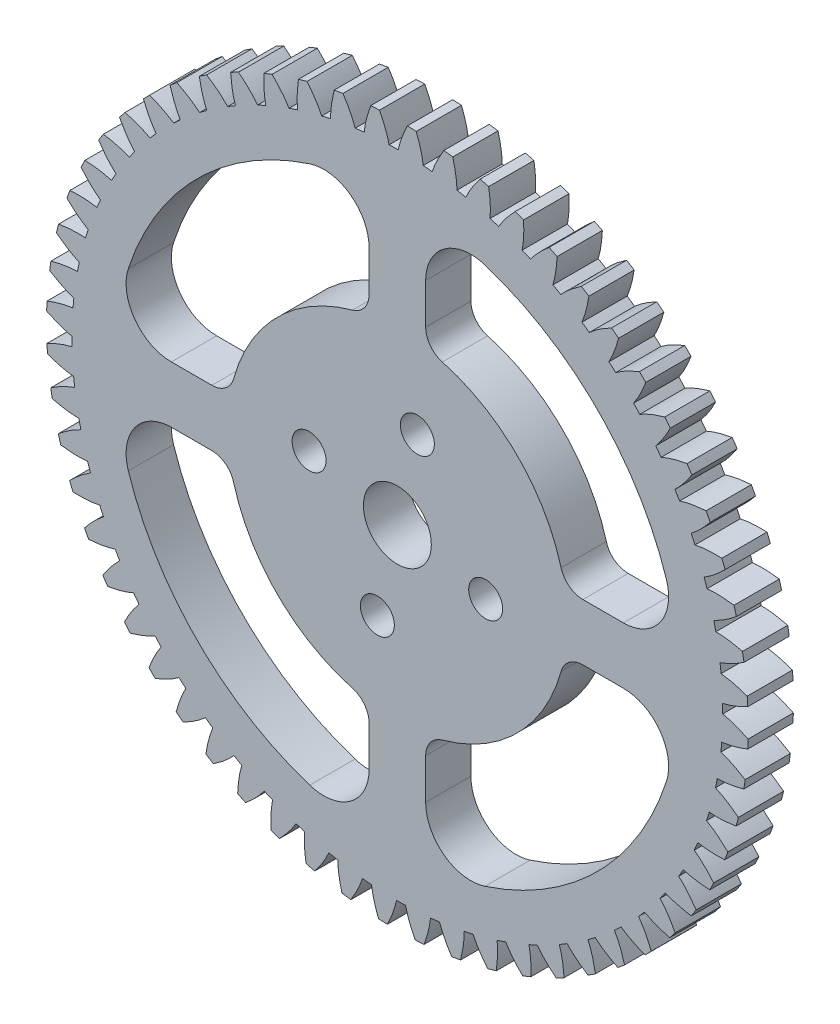
SolidWorks part; units mm, degrees
ref_plane "前视基准面" through (0, 0, 0) normal (0, 0, 1) x (1, 0, 0)
ref_plane "上视基准面" through (0, 0, 0) normal (0, 1, 0) x (1, 0, 0)
ref_plane "右视基准面" through (0, 0, 0) normal (1, 0, 0) x (0, 0, -1)
other "Configuration Table"
sketch "草图4" plane through (0, 0, 0) normal (0, 0, 1) x (1, 0, 0)
  line L0 (0, 0) -> (1.2733, 30.9738) construction
  line L1 (0, 0) -> (0.4471, 29.9967) construction
  line L2 (0, 0) -> (2.8926, 30.8648) construction
  circle A0 centre (0, 0) radius 30
  circle A1 centre (0, 0) radius 31
  circle A2 centre (0, 0) radius 28.75
  spline S0 degree 4 poles (0, 28.1908) (0.0005, 28.2136) (0.0035, 28.2777) (0.0153, 28.3985) (0.0434, 28.5946) (0.1142, 28.9567) (0.2601, 29.498) (0.4684, 30.082) (0.7305, 30.6867) (0.9882, 31.2083) (1.2086, 31.6182) (1.4921, 32.1066) (1.8568, 32.6819) (2.3141, 33.3354) (2.8753, 34.0567) (3.4818, 34.7632) (4.1191, 35.4414) (4.7852, 36.0922) (5.4762, 36.7151) (6.1025, 37.2372) (6.6509, 37.6668) (7.1192, 38.0155) (7.4936, 38.2848) (7.8829, 38.5536) (8.2582, 38.8052) (8.6695, 39.0687) (9.0299, 39.2939) (9.5696, 39.6154) (9.8959, 39.8017) (10.4233, 40.0948) (10.6619, 40.2173) (10.8772, 40.3318) (10.941, 40.3633) (10.9876, 40.3874) (11.0127, 40.4005) knots 0 0 0 0 0 0.005377 0.015084 0.028532 0.04661 0.092111 0.146842 0.174209 0.201575 0.228941 0.256307 0.307035 0.361767 0.4165 0.471232 0.525964 0.580697 0.635429 0.690161 0.717528 0.744894 0.77226 0.799626 0.826992 0.854358 0.881725 0.909091 0.954545 0.977273 0.988636 0.994318 1 1 1 1 1 construction
  spline S1 degree 4 poles (0.0751, 28.7499) (0.0864, 28.8057) (0.1395, 29.0504) (0.2668, 29.5168) (0.4673, 30.079) (0.6816, 30.574) (0.8307, 30.886) (0.8807, 30.9875) knots 0.033216 0.033216 0.033216 0.033216 0.033216 0.04661 0.092111 0.146842 0.173451 0.173451 0.173451 0.173451 0.173451
  spline S2 degree 4 poles (2.2849, 28.6591) (2.2782, 28.7156) (2.2453, 28.9638) (2.1567, 29.4391) (2.003, 30.0158) (1.8301, 30.5268) (1.7071, 30.85) (1.6656, 30.9552) knots 0.033216 0.033216 0.033216 0.033216 0.033216 0.04661 0.092111 0.146842 0.173451 0.173451 0.173451 0.173451 0.173451
  spline S3 degree 4 poles (3.0798, 28.5846) (3.0969, 28.6389) (3.1753, 28.8767) (3.3507, 29.3272) (3.6089, 29.8653) (3.8738, 30.3353) (4.0546, 30.63) (4.1149, 30.7257) knots 0.033216 0.033216 0.033216 0.033216 0.033216 0.04661 0.092111 0.146842 0.173451 0.173451 0.173451 0.173451 0.173451
  dimension "D1" = 60
  dimension "D2" = 62
  dimension "D3" = 57.5
  dimension "D5" = 1.5
  dimension "D6" = 4.5
sketch "草图6" plane through (0, 0, 0) normal (0, 0, 1) x (1, 0, 0)
  circle A0 centre (0, 0) radius 28.75 construction
  circle A1 centre (0, 0) radius 31 construction
  arc A2 (3.0798, 28.5846) -> (2.2849, 28.6591) centre (0, 0) ccw
  arc A3 (1.6656, 30.9552) -> (0.8807, 30.9875) centre (0, 0) ccw
  arc A4 (4.8922, 30.6115) -> (4.1149, 30.7257) centre (0, 0) ccw
  arc A5 (6.0509, 28.106) -> (5.268, 28.2632) centre (0, 0) ccw
  arc A6 (8.0652, 29.9325) -> (7.3041, 30.1272) centre (0, 0) ccw
  arc A7 (8.9556, 27.3196) -> (8.1935, 27.5577) centre (0, 0) ccw
  arc A8 (11.1498, 28.9255) -> (10.4132, 29.1987) centre (0, 0) ccw
  arc A9 (11.7622, 26.2338) -> (11.0292, 26.5503) centre (0, 0) ccw
  arc A10 (14.1123, 27.6015) -> (13.4083, 27.9503) centre (0, 0) ccw
  arc A11 (14.44, 24.8606) -> (13.744, 25.252) centre (0, 0) ccw
  arc A12 (16.9201, 25.9752) -> (16.2564, 26.3956) centre (0, 0) ccw
  arc A13 (16.9595, 23.215) -> (16.3083, 23.677) centre (0, 0) ccw
  arc A14 (19.5426, 24.0643) -> (18.9265, 24.5518) centre (0, 0) ccw
  arc A15 (19.2932, 21.3151) -> (18.6939, 21.8427) centre (0, 0) ccw
  arc A16 (21.9509, 21.8897) -> (21.3891, 22.4389) centre (0, 0) ccw
  arc A17 (21.4156, 19.1817) -> (20.8747, 19.769) centre (0, 0) ccw
  arc A18 (24.1187, 19.4753) -> (23.6175, 20.0802) centre (0, 0) ccw
  arc A19 (23.3033, 16.838) -> (22.8267, 17.4787) centre (0, 0) ccw
  arc A20 (26.0223, 16.8475) -> (25.587, 17.5015) centre (0, 0) ccw
  arc A21 (24.9357, 14.31) -> (24.5287, 14.9969) centre (0, 0) ccw
  arc A22 (27.6408, 14.0351) -> (27.2763, 14.7311) centre (0, 0) ccw
  arc A23 (26.2949, 11.6251) -> (25.9619, 12.3508) centre (0, 0) ccw
  arc A24 (28.9565, 11.069) -> (28.6667, 11.7992) centre (0, 0) ccw
  arc A25 (27.366, 8.8128) -> (27.1107, 9.5694) centre (0, 0) ccw
  arc A26 (29.9549, 7.9816) -> (29.743, 8.7381) centre (0, 0) ccw
  arc A27 (28.1373, 5.904) -> (27.9625, 6.6831) centre (0, 0) ccw
  arc A28 (30.6251, 4.8067) -> (30.4934, 5.5812) centre (0, 0) ccw
  arc A29 (28.6003, 2.9305) -> (28.5078, 3.7236) centre (0, 0) ccw
  arc A30 (30.9598, 1.5792) -> (30.9098, 2.3632) centre (0, 0) ccw
  arc A31 (28.7499, -0.0751) -> (28.7409, 0.7233) centre (0, 0) ccw
  arc A32 (30.9552, -1.6656) -> (30.9875, -0.8807) centre (0, 0) ccw
  arc A33 (28.5846, -3.0798) -> (28.6591, -2.2849) centre (0, 0) ccw
  arc A34 (30.6115, -4.8922) -> (30.7257, -4.1149) centre (0, 0) ccw
  arc A35 (28.106, -6.0509) -> (28.2632, -5.268) centre (0, 0) ccw
  arc A36 (29.9325, -8.0652) -> (30.1272, -7.3041) centre (0, 0) ccw
  arc A37 (27.3196, -8.9556) -> (27.5577, -8.1935) centre (0, 0) ccw
  arc A38 (28.9255, -11.1498) -> (29.1987, -10.4132) centre (0, 0) ccw
  arc A39 (26.2338, -11.7622) -> (26.5503, -11.0292) centre (0, 0) ccw
  arc A40 (27.6015, -14.1123) -> (27.9503, -13.4083) centre (0, 0) ccw
  arc A41 (24.8606, -14.44) -> (25.252, -13.744) centre (0, 0) ccw
  arc A42 (25.9752, -16.9201) -> (26.3956, -16.2564) centre (0, 0) ccw
  arc A43 (23.215, -16.9595) -> (23.677, -16.3083) centre (0, 0) ccw
  arc A44 (24.0643, -19.5426) -> (24.5518, -18.9265) centre (0, 0) ccw
  arc A45 (21.3151, -19.2932) -> (21.8427, -18.6939) centre (0, 0) ccw
  arc A46 (21.8897, -21.9509) -> (22.4389, -21.3891) centre (0, 0) ccw
  arc A47 (19.1817, -21.4156) -> (19.769, -20.8747) centre (0, 0) ccw
  arc A48 (19.4753, -24.1187) -> (20.0802, -23.6175) centre (0, 0) ccw
  arc A49 (16.838, -23.3033) -> (17.4787, -22.8267) centre (0, 0) ccw
  arc A50 (16.8475, -26.0223) -> (17.5015, -25.587) centre (0, 0) ccw
  arc A51 (14.31, -24.9357) -> (14.9969, -24.5287) centre (0, 0) ccw
  arc A52 (14.0351, -27.6408) -> (14.7311, -27.2763) centre (0, 0) ccw
  arc A53 (11.6251, -26.2949) -> (12.3508, -25.9619) centre (0, 0) ccw
  arc A54 (11.069, -28.9565) -> (11.7992, -28.6667) centre (0, 0) ccw
  arc A55 (8.8128, -27.366) -> (9.5694, -27.1107) centre (0, 0) ccw
  arc A56 (7.9816, -29.9549) -> (8.7381, -29.743) centre (0, 0) ccw
  arc A57 (5.904, -28.1373) -> (6.6831, -27.9625) centre (0, 0) ccw
  arc A58 (4.8067, -30.6251) -> (5.5812, -30.4934) centre (0, 0) ccw
  arc A59 (2.9305, -28.6003) -> (3.7236, -28.5078) centre (0, 0) ccw
  arc A60 (1.5792, -30.9598) -> (2.3632, -30.9098) centre (0, 0) ccw
  arc A61 (-0.0751, -28.7499) -> (0.7233, -28.7409) centre (0, 0) ccw
  arc A62 (-1.6656, -30.9552) -> (-0.8807, -30.9875) centre (0, 0) ccw
  arc A63 (-3.0798, -28.5846) -> (-2.2849, -28.6591) centre (0, 0) ccw
  arc A64 (-4.8922, -30.6115) -> (-4.1149, -30.7257) centre (0, 0) ccw
  arc A65 (-6.0509, -28.106) -> (-5.268, -28.2632) centre (0, 0) ccw
  arc A66 (-8.0652, -29.9325) -> (-7.3041, -30.1272) centre (0, 0) ccw
  arc A67 (-8.9556, -27.3196) -> (-8.1935, -27.5577) centre (0, 0) ccw
  arc A68 (-11.1498, -28.9255) -> (-10.4132, -29.1987) centre (0, 0) ccw
  arc A69 (-11.7622, -26.2338) -> (-11.0292, -26.5503) centre (0, 0) ccw
  arc A70 (-14.1123, -27.6015) -> (-13.4083, -27.9503) centre (0, 0) ccw
  arc A71 (-14.44, -24.8606) -> (-13.744, -25.252) centre (0, 0) ccw
  arc A72 (-16.9201, -25.9752) -> (-16.2564, -26.3956) centre (0, 0) ccw
  arc A73 (-16.9595, -23.215) -> (-16.3083, -23.677) centre (0, 0) ccw
  arc A74 (-19.5426, -24.0643) -> (-18.9265, -24.5518) centre (0, 0) ccw
  arc A75 (-19.2932, -21.3151) -> (-18.6939, -21.8427) centre (0, 0) ccw
  arc A76 (-21.9509, -21.8897) -> (-21.3891, -22.4389) centre (0, 0) ccw
  arc A77 (-21.4156, -19.1817) -> (-20.8747, -19.769) centre (0, 0) ccw
  arc A78 (-24.1187, -19.4753) -> (-23.6175, -20.0802) centre (0, 0) ccw
  arc A79 (-23.3033, -16.838) -> (-22.8267, -17.4787) centre (0, 0) ccw
  arc A80 (-26.0223, -16.8475) -> (-25.587, -17.5015) centre (0, 0) ccw
  arc A81 (-24.9357, -14.31) -> (-24.5287, -14.9969) centre (0, 0) ccw
  arc A82 (-27.6408, -14.0351) -> (-27.2763, -14.7311) centre (0, 0) ccw
  arc A83 (-26.2949, -11.6251) -> (-25.9619, -12.3508) centre (0, 0) ccw
  arc A84 (-28.9565, -11.069) -> (-28.6667, -11.7992) centre (0, 0) ccw
  arc A85 (-27.366, -8.8128) -> (-27.1107, -9.5694) centre (0, 0) ccw
  arc A86 (-29.9549, -7.9816) -> (-29.743, -8.7381) centre (0, 0) ccw
  arc A87 (-28.1373, -5.904) -> (-27.9625, -6.6831) centre (0, 0) ccw
  arc A88 (-30.6251, -4.8067) -> (-30.4934, -5.5812) centre (0, 0) ccw
  arc A89 (-28.6003, -2.9305) -> (-28.5078, -3.7236) centre (0, 0) ccw
  arc A90 (-30.9598, -1.5792) -> (-30.9098, -2.3632) centre (0, 0) ccw
  arc A91 (-28.7499, 0.0751) -> (-28.7409, -0.7233) centre (0, 0) ccw
  arc A92 (-30.9552, 1.6656) -> (-30.9875, 0.8807) centre (0, 0) ccw
  arc A93 (-28.5846, 3.0798) -> (-28.6591, 2.2849) centre (0, 0) ccw
  arc A94 (-30.6115, 4.8922) -> (-30.7257, 4.1149) centre (0, 0) ccw
  arc A95 (-28.106, 6.0509) -> (-28.2632, 5.268) centre (0, 0) ccw
  arc A96 (-29.9325, 8.0652) -> (-30.1272, 7.3041) centre (0, 0) ccw
  arc A97 (-27.3196, 8.9556) -> (-27.5577, 8.1935) centre (0, 0) ccw
  arc A98 (-28.9255, 11.1498) -> (-29.1987, 10.4132) centre (0, 0) ccw
  arc A99 (-26.2338, 11.7622) -> (-26.5503, 11.0292) centre (0, 0) ccw
  arc A100 (-27.6015, 14.1123) -> (-27.9503, 13.4083) centre (0, 0) ccw
  arc A101 (-24.8606, 14.44) -> (-25.252, 13.744) centre (0, 0) ccw
  arc A102 (-25.9752, 16.9201) -> (-26.3956, 16.2564) centre (0, 0) ccw
  arc A103 (-23.215, 16.9595) -> (-23.677, 16.3083) centre (0, 0) ccw
  arc A104 (-24.0643, 19.5426) -> (-24.5518, 18.9265) centre (0, 0) ccw
  arc A105 (-21.3151, 19.2932) -> (-21.8427, 18.6939) centre (0, 0) ccw
  arc A106 (-21.8897, 21.9509) -> (-22.4389, 21.3891) centre (0, 0) ccw
  arc A107 (-19.1817, 21.4156) -> (-19.769, 20.8747) centre (0, 0) ccw
  arc A108 (-19.4753, 24.1187) -> (-20.0802, 23.6175) centre (0, 0) ccw
  arc A109 (-16.838, 23.3033) -> (-17.4787, 22.8267) centre (0, 0) ccw
  arc A110 (-16.8475, 26.0223) -> (-17.5015, 25.587) centre (0, 0) ccw
  arc A111 (-14.31, 24.9357) -> (-14.9969, 24.5287) centre (0, 0) ccw
  arc A112 (-14.0351, 27.6408) -> (-14.7311, 27.2763) centre (0, 0) ccw
  arc A113 (-11.6251, 26.2949) -> (-12.3508, 25.9619) centre (0, 0) ccw
  arc A114 (-11.069, 28.9565) -> (-11.7992, 28.6667) centre (0, 0) ccw
  arc A115 (-8.8128, 27.366) -> (-9.5694, 27.1107) centre (0, 0) ccw
  arc A116 (-7.9816, 29.9549) -> (-8.7381, 29.743) centre (0, 0) ccw
  arc A117 (-5.904, 28.1373) -> (-6.6831, 27.9625) centre (0, 0) ccw
  arc A118 (-4.8067, 30.6251) -> (-5.5812, 30.4934) centre (0, 0) ccw
  arc A119 (-2.9305, 28.6003) -> (-3.7236, 28.5078) centre (0, 0) ccw
  arc A120 (-1.5792, 30.9598) -> (-2.3632, 30.9098) centre (0, 0) ccw
  arc A121 (0.0751, 28.7499) -> (-0.7233, 28.7409) centre (0, 0) ccw
  spline S1 degree 4 poles (-2989.4472, 249.0718) (-36.0188, 13.9485) (0.3459, 18.5122) (3.419, 24.7025) (-1.9267, 44.7617) (-35.0804, 50.8867) (80.2851, 37.967) (-2996.7297, 123.8003) knots -1.11848 -1.11848 -1.11848 -1.11848 -1.11848 0.04661 0.092111 0.146842 3.758916 3.758916 3.758916 3.758916 3.758916 only from (2.2849, 28.6591) to (1.6656, 30.9552) construction
  spline S2 degree 4 poles (2999.8038, 2.8693) (37.0421, 10.9451) (1.1746, 18.4782) (-1.38, 24.8998) (5.5941, 44.4525) (39.1386, 47.8358) (-76.898, 44.4284) (2996.78, -122.5772) knots -1.11848 -1.11848 -1.11848 -1.11848 -1.11848 0.04661 0.092111 0.146842 3.758916 3.758916 3.758916 3.758916 3.758916 only from (0.0751, 28.7499) to (0.8807, 30.9875) construction
  spline S3 degree 4 poles (3.0798, 28.5846) (3.0969, 28.6389) (3.1753, 28.8767) (3.3507, 29.3272) (3.6089, 29.8653) (3.8738, 30.3353) (4.0546, 30.63) (4.1149, 30.7257) knots 0.033216 0.033216 0.033216 0.033216 0.033216 0.04661 0.092111 0.146842 0.173451 0.173451 0.173451 0.173451 0.173451
  spline S4 degree 4 poles (2.2849, 28.6591) (2.2782, 28.7156) (2.2453, 28.9638) (2.1567, 29.4391) (2.003, 30.0158) (1.8301, 30.5268) (1.7071, 30.85) (1.6656, 30.9552) knots 0.033216 0.033216 0.033216 0.033216 0.033216 0.04661 0.092111 0.146842 0.173451 0.173451 0.173451 0.173451 0.173451
  spline S5 degree 4 poles (0.0751, 28.7499) (0.0864, 28.8057) (0.1395, 29.0504) (0.2668, 29.5168) (0.4673, 30.079) (0.6816, 30.574) (0.8307, 30.886) (0.8807, 30.9875) knots 0.033216 0.033216 0.033216 0.033216 0.033216 0.04661 0.092111 0.146842 0.173451 0.173451 0.173451 0.173451 0.173451
  spline S6 degree 4 poles (5.268, 28.2632) (5.2673, 28.3202) (5.2605, 28.5705) (5.2221, 29.0524) (5.1296, 29.642) (5.0109, 30.1683) (4.9224, 30.5025) (4.8922, 30.6115) knots 0.033216 0.033216 0.033216 0.033216 0.033216 0.04661 0.092111 0.146842 0.173451 0.173451 0.173451 0.173451 0.173451
  spline S7 degree 4 poles (6.0509, 28.106) (6.0735, 28.1583) (6.1764, 28.3866) (6.3978, 28.8163) (6.7109, 29.3245) (7.0234, 29.7642) (7.2341, 30.0384) (7.3041, 30.1272) knots 0.033216 0.033216 0.033216 0.033216 0.033216 0.04661 0.092111 0.146842 0.173451 0.173451 0.173451 0.173451 0.173451
  spline S8 degree 4 poles (8.1935, 27.5577) (8.1987, 27.6144) (8.2182, 27.8641) (8.2303, 28.3474) (8.1999, 28.9435) (8.1369, 29.4792) (8.0839, 29.8209) (8.0652, 29.9325) knots 0.033216 0.033216 0.033216 0.033216 0.033216 0.04661 0.092111 0.146842 0.173451 0.173451 0.173451 0.173451 0.173451
  spline S9 degree 4 poles (8.9556, 27.3196) (8.9836, 27.3692) (9.1097, 27.5854) (9.3749, 27.9897) (9.7393, 28.4624) (10.0962, 28.867) (10.3344, 29.1176) (10.4132, 29.1987) knots 0.033216 0.033216 0.033216 0.033216 0.033216 0.04661 0.092111 0.146842 0.173451 0.173451 0.173451 0.173451 0.173451
  spline S10 degree 4 poles (11.0292, 26.5503) (11.0403, 26.6062) (11.0857, 26.8524) (11.1483, 27.3318) (11.1804, 27.9278) (11.1738, 28.4672) (11.1567, 28.8126) (11.1498, 28.9255) knots 0.033216 0.033216 0.033216 0.033216 0.033216 0.04661 0.092111 0.146842 0.173451 0.173451 0.173451 0.173451 0.173451
  spline S11 degree 4 poles (11.7622, 26.2338) (11.7952, 26.2802) (11.9433, 26.4821) (12.2493, 26.8564) (12.6611, 27.2884) (13.0583, 27.6535) (13.3214, 27.8779) (13.4083, 27.9503) knots 0.033216 0.033216 0.033216 0.033216 0.033216 0.04661 0.092111 0.146842 0.173451 0.173451 0.173451 0.173451 0.173451
  spline S12 degree 4 poles (13.744, 25.252) (13.7609, 25.3064) (13.8318, 25.5465) (13.9442, 26.0167) (14.0384, 26.6061) (14.0882, 27.1433) (14.1073, 27.4885) (14.1123, 27.6015) knots 0.033216 0.033216 0.033216 0.033216 0.033216 0.04661 0.092111 0.146842 0.173451 0.173451 0.173451 0.173451 0.173451
  spline S13 degree 4 poles (14.44, 24.8606) (14.4777, 24.9033) (14.646, 25.0886) (14.9894, 25.4289) (15.4442, 25.8155) (15.8773, 26.1371) (16.1624, 26.3327) (16.2564, 26.3956) knots 0.033216 0.033216 0.033216 0.033216 0.033216 0.04661 0.092111 0.146842 0.173451 0.173451 0.173451 0.173451 0.173451
  spline S14 degree 4 poles (16.3083, 23.677) (16.3308, 23.7294) (16.4264, 23.9608) (16.5873, 24.4166) (16.7426, 24.993) (16.8483, 25.522) (16.9034, 25.8633) (16.9201, 25.9752) knots 0.033216 0.033216 0.033216 0.033216 0.033216 0.04661 0.092111 0.146842 0.173451 0.173451 0.173451 0.173451 0.173451
  spline S15 degree 4 poles (16.9595, 23.215) (17.0015, 23.2535) (17.1883, 23.4202) (17.5654, 23.7228) (18.058, 24.0597) (18.5224, 24.3342) (18.8264, 24.499) (18.9265, 24.5518) knots 0.033216 0.033216 0.033216 0.033216 0.033216 0.04661 0.092111 0.146842 0.173451 0.173451 0.173451 0.173451 0.173451
  spline S16 degree 4 poles (18.6939, 21.8427) (18.7217, 21.8923) (18.841, 22.1125) (19.0487, 22.549) (19.2633, 23.106) (19.4237, 23.621) (19.5142, 23.9548) (19.5426, 24.0643) knots 0.033216 0.033216 0.033216 0.033216 0.033216 0.04661 0.092111 0.146842 0.173451 0.173451 0.173451 0.173451 0.173451
  spline S17 degree 4 poles (19.2932, 21.3151) (19.339, 21.349) (19.5422, 21.4953) (19.9488, 21.7567) (20.474, 22.0403) (20.9646, 22.2648) (21.2841, 22.3969) (21.3891, 22.4389) knots 0.033216 0.033216 0.033216 0.033216 0.033216 0.04661 0.092111 0.146842 0.173451 0.173451 0.173451 0.173451 0.173451
  spline S18 degree 4 poles (20.8747, 19.769) (20.9075, 19.8155) (21.0492, 20.0219) (21.3014, 20.4344) (21.573, 20.9658) (21.7864, 21.4613) (21.9113, 21.7837) (21.9509, 21.8897) knots 0.033216 0.033216 0.033216 0.033216 0.033216 0.04661 0.092111 0.146842 0.173451 0.173451 0.173451 0.173451 0.173451
  spline S19 degree 4 poles (21.4156, 19.1817) (21.4646, 19.2106) (21.682, 19.3348) (22.1138, 19.5523) (22.6657, 19.7795) (23.177, 19.9514) (23.5086, 20.0494) (23.6175, 20.0802) knots 0.033216 0.033216 0.033216 0.033216 0.033216 0.04661 0.092111 0.146842 0.173451 0.173451 0.173451 0.173451 0.173451
  spline S20 degree 4 poles (22.8267, 17.4787) (22.8642, 17.5215) (23.0267, 17.712) (23.3206, 18.0958) (23.6464, 18.596) (23.9104, 19.0664) (24.0683, 19.3741) (24.1187, 19.4753) knots 0.033216 0.033216 0.033216 0.033216 0.033216 0.04661 0.092111 0.146842 0.173451 0.173451 0.173451 0.173451 0.173451
  spline S21 degree 4 poles (23.3033, 16.838) (23.3551, 16.8617) (23.5843, 16.9625) (24.0364, 17.1337) (24.6091, 17.3019) (25.1356, 17.4195) (25.4756, 17.4823) (25.587, 17.5015) knots 0.033216 0.033216 0.033216 0.033216 0.033216 0.04661 0.092111 0.146842 0.173451 0.173451 0.173451 0.173451 0.173451
  spline S22 degree 4 poles (24.5287, 14.9969) (24.5705, 15.0355) (24.752, 15.208) (25.0844, 15.559) (25.4607, 16.0224) (25.7724, 16.4627) (25.9616, 16.7521) (26.0223, 16.8475) knots 0.033216 0.033216 0.033216 0.033216 0.033216 0.04661 0.092111 0.146842 0.173451 0.173451 0.173451 0.173451 0.173451
  spline S23 degree 4 poles (24.9357, 14.31) (24.9897, 14.328) (25.2281, 14.4044) (25.6957, 14.5273) (26.2828, 14.6348) (26.8187, 14.6967) (27.1634, 14.7236) (27.2763, 14.7311) knots 0.033216 0.033216 0.033216 0.033216 0.033216 0.04661 0.092111 0.146842 0.173451 0.173451 0.173451 0.173451 0.173451
  spline S24 degree 4 poles (25.9619, 12.3508) (26.0075, 12.3849) (26.2061, 12.5374) (26.5734, 12.8518) (26.996, 13.2732) (27.352, 13.6785) (27.5704, 13.9466) (27.6408, 14.0351) knots 0.033216 0.033216 0.033216 0.033216 0.033216 0.04661 0.092111 0.146842 0.173451 0.173451 0.173451 0.173451 0.173451
  spline S25 degree 4 poles (26.2949, 11.6251) (26.3505, 11.6374) (26.5956, 11.6884) (27.0734, 11.7618) (27.6686, 11.8073) (28.208, 11.8129) (28.5537, 11.8036) (28.6667, 11.7992) knots 0.033216 0.033216 0.033216 0.033216 0.033216 0.04661 0.092111 0.146842 0.173451 0.173451 0.173451 0.173451 0.173451
  spline S26 degree 4 poles (27.1107, 9.5694) (27.1596, 9.5985) (27.373, 9.7295) (27.7712, 10.0037) (28.2355, 10.3787) (28.632, 10.7445) (28.8772, 10.9883) (28.9565, 11.069) knots 0.033216 0.033216 0.033216 0.033216 0.033216 0.04661 0.092111 0.146842 0.173451 0.173451 0.173451 0.173451 0.173451
  spline S27 degree 4 poles (27.366, 8.8128) (27.4225, 8.8193) (27.6717, 8.8444) (28.1546, 8.8674) (28.7512, 8.8505) (29.2883, 8.7996) (29.631, 8.7542) (29.743, 8.7381) knots 0.033216 0.033216 0.033216 0.033216 0.033216 0.04661 0.092111 0.146842 0.173451 0.173451 0.173451 0.173451 0.173451
  spline S28 degree 4 poles (27.9625, 6.6831) (28.0142, 6.7069) (28.2401, 6.8149) (28.6647, 7.046) (29.1657, 7.3704) (29.5982, 7.6928) (29.8676, 7.9096) (29.9549, 7.9816) knots 0.033216 0.033216 0.033216 0.033216 0.033216 0.04661 0.092111 0.146842 0.173451 0.173451 0.173451 0.173451 0.173451
  spline S29 degree 4 poles (28.1373, 5.904) (28.1942, 5.9045) (28.4446, 5.9034) (28.9272, 5.8759) (29.5188, 5.7967) (30.0476, 5.6899) (30.3838, 5.609) (30.4934, 5.5812) knots 0.033216 0.033216 0.033216 0.033216 0.033216 0.04661 0.092111 0.146842 0.173451 0.173451 0.173451 0.173451 0.173451
  spline S30 degree 4 poles (28.5078, 3.7236) (28.5618, 3.7419) (28.7977, 3.8257) (29.2442, 4.0111) (29.7764, 4.2814) (30.2402, 4.5568) (30.5308, 4.7443) (30.6251, 4.8067) knots 0.033216 0.033216 0.033216 0.033216 0.033216 0.04661 0.092111 0.146842 0.173451 0.173451 0.173451 0.173451 0.173451
  spline S31 degree 4 poles (28.6003, 2.9305) (28.6569, 2.9251) (28.9058, 2.8978) (29.383, 2.82) (29.963, 2.6794) (30.4778, 2.5179) (30.8036, 2.4023) (30.9098, 2.3632) knots 0.033216 0.033216 0.033216 0.033216 0.033216 0.04661 0.092111 0.146842 0.173451 0.173451 0.173451 0.173451 0.173451
  spline S32 degree 4 poles (28.7409, 0.7233) (28.7964, 0.7359) (29.0398, 0.7945) (29.5033, 0.9323) (30.0608, 1.1455) (30.5509, 1.3709) (30.8594, 1.527) (30.9598, 1.5792) knots 0.033216 0.033216 0.033216 0.033216 0.033216 0.04661 0.092111 0.146842 0.173451 0.173451 0.173451 0.173451 0.173451
  spline S33 degree 4 poles (28.7499, -0.0751) (28.8057, -0.0864) (29.0504, -0.1395) (29.5168, -0.2668) (30.079, -0.4673) (30.574, -0.6816) (30.886, -0.8307) (30.9875, -0.8807) knots 0.033216 0.033216 0.033216 0.033216 0.033216 0.04661 0.092111 0.146842 0.173451 0.173451 0.173451 0.173451 0.173451
  spline S34 degree 4 poles (28.6591, -2.2849) (28.7156, -2.2782) (28.9638, -2.2453) (29.4391, -2.1567) (30.0158, -2.003) (30.5268, -1.8301) (30.85, -1.7071) (30.9552, -1.6656) knots 0.033216 0.033216 0.033216 0.033216 0.033216 0.04661 0.092111 0.146842 0.173451 0.173451 0.173451 0.173451 0.173451
  spline S35 degree 4 poles (28.5846, -3.0798) (28.6389, -3.0969) (28.8767, -3.1753) (29.3272, -3.3507) (29.8653, -3.6089) (30.3353, -3.8738) (30.63, -4.0546) (30.7257, -4.1149) knots 0.033216 0.033216 0.033216 0.033216 0.033216 0.04661 0.092111 0.146842 0.173451 0.173451 0.173451 0.173451 0.173451
  spline S36 degree 4 poles (28.2632, -5.268) (28.3202, -5.2673) (28.5705, -5.2605) (29.0524, -5.2221) (29.642, -5.1296) (30.1683, -5.0109) (30.5025, -4.9224) (30.6115, -4.8922) knots 0.033216 0.033216 0.033216 0.033216 0.033216 0.04661 0.092111 0.146842 0.173451 0.173451 0.173451 0.173451 0.173451
  spline S37 degree 4 poles (28.106, -6.0509) (28.1583, -6.0735) (28.3866, -6.1764) (28.8163, -6.3978) (29.3245, -6.7109) (29.7642, -7.0234) (30.0384, -7.2341) (30.1272, -7.3041) knots 0.033216 0.033216 0.033216 0.033216 0.033216 0.04661 0.092111 0.146842 0.173451 0.173451 0.173451 0.173451 0.173451
  spline S38 degree 4 poles (27.5577, -8.1935) (27.6144, -8.1987) (27.8641, -8.2182) (28.3474, -8.2303) (28.9435, -8.1999) (29.4792, -8.1369) (29.8209, -8.0839) (29.9325, -8.0652) knots 0.033216 0.033216 0.033216 0.033216 0.033216 0.04661 0.092111 0.146842 0.173451 0.173451 0.173451 0.173451 0.173451
  spline S39 degree 4 poles (27.3196, -8.9556) (27.3692, -8.9836) (27.5854, -9.1097) (27.9897, -9.3749) (28.4624, -9.7393) (28.867, -10.0962) (29.1176, -10.3344) (29.1987, -10.4132) knots 0.033216 0.033216 0.033216 0.033216 0.033216 0.04661 0.092111 0.146842 0.173451 0.173451 0.173451 0.173451 0.173451
  spline S40 degree 4 poles (26.5503, -11.0292) (26.6062, -11.0403) (26.8524, -11.0857) (27.3318, -11.1483) (27.9278, -11.1804) (28.4672, -11.1738) (28.8126, -11.1567) (28.9255, -11.1498) knots 0.033216 0.033216 0.033216 0.033216 0.033216 0.04661 0.092111 0.146842 0.173451 0.173451 0.173451 0.173451 0.173451
  spline S41 degree 4 poles (26.2338, -11.7622) (26.2802, -11.7952) (26.4821, -11.9433) (26.8564, -12.2493) (27.2884, -12.6611) (27.6535, -13.0583) (27.8779, -13.3214) (27.9503, -13.4083) knots 0.033216 0.033216 0.033216 0.033216 0.033216 0.04661 0.092111 0.146842 0.173451 0.173451 0.173451 0.173451 0.173451
  spline S42 degree 4 poles (25.252, -13.744) (25.3064, -13.7609) (25.5465, -13.8318) (26.0167, -13.9442) (26.6061, -14.0384) (27.1433, -14.0882) (27.4885, -14.1073) (27.6015, -14.1123) knots 0.033216 0.033216 0.033216 0.033216 0.033216 0.04661 0.092111 0.146842 0.173451 0.173451 0.173451 0.173451 0.173451
  spline S43 degree 4 poles (24.8606, -14.44) (24.9033, -14.4777) (25.0886, -14.646) (25.4289, -14.9894) (25.8155, -15.4442) (26.1371, -15.8773) (26.3327, -16.1624) (26.3956, -16.2564) knots 0.033216 0.033216 0.033216 0.033216 0.033216 0.04661 0.092111 0.146842 0.173451 0.173451 0.173451 0.173451 0.173451
  spline S44 degree 4 poles (23.677, -16.3083) (23.7294, -16.3308) (23.9608, -16.4264) (24.4166, -16.5873) (24.993, -16.7426) (25.522, -16.8483) (25.8633, -16.9034) (25.9752, -16.9201) knots 0.033216 0.033216 0.033216 0.033216 0.033216 0.04661 0.092111 0.146842 0.173451 0.173451 0.173451 0.173451 0.173451
  spline S45 degree 4 poles (23.215, -16.9595) (23.2535, -17.0015) (23.4202, -17.1883) (23.7228, -17.5654) (24.0597, -18.058) (24.3342, -18.5224) (24.499, -18.8264) (24.5518, -18.9265) knots 0.033216 0.033216 0.033216 0.033216 0.033216 0.04661 0.092111 0.146842 0.173451 0.173451 0.173451 0.173451 0.173451
  spline S46 degree 4 poles (21.8427, -18.6939) (21.8923, -18.7217) (22.1125, -18.841) (22.549, -19.0487) (23.106, -19.2633) (23.621, -19.4237) (23.9548, -19.5142) (24.0643, -19.5426) knots 0.033216 0.033216 0.033216 0.033216 0.033216 0.04661 0.092111 0.146842 0.173451 0.173451 0.173451 0.173451 0.173451
  spline S47 degree 4 poles (21.3151, -19.2932) (21.349, -19.339) (21.4953, -19.5422) (21.7567, -19.9488) (22.0403, -20.474) (22.2648, -20.9646) (22.3969, -21.2841) (22.4389, -21.3891) knots 0.033216 0.033216 0.033216 0.033216 0.033216 0.04661 0.092111 0.146842 0.173451 0.173451 0.173451 0.173451 0.173451
  spline S48 degree 4 poles (19.769, -20.8747) (19.8155, -20.9075) (20.0219, -21.0492) (20.4344, -21.3014) (20.9658, -21.573) (21.4613, -21.7864) (21.7837, -21.9113) (21.8897, -21.9509) knots 0.033216 0.033216 0.033216 0.033216 0.033216 0.04661 0.092111 0.146842 0.173451 0.173451 0.173451 0.173451 0.173451
  spline S49 degree 4 poles (19.1817, -21.4156) (19.2106, -21.4646) (19.3348, -21.682) (19.5523, -22.1138) (19.7795, -22.6657) (19.9514, -23.177) (20.0494, -23.5086) (20.0802, -23.6175) knots 0.033216 0.033216 0.033216 0.033216 0.033216 0.04661 0.092111 0.146842 0.173451 0.173451 0.173451 0.173451 0.173451
  spline S50 degree 4 poles (17.4787, -22.8267) (17.5215, -22.8642) (17.712, -23.0267) (18.0958, -23.3206) (18.596, -23.6464) (19.0664, -23.9104) (19.3741, -24.0683) (19.4753, -24.1187) knots 0.033216 0.033216 0.033216 0.033216 0.033216 0.04661 0.092111 0.146842 0.173451 0.173451 0.173451 0.173451 0.173451
  spline S51 degree 4 poles (16.838, -23.3033) (16.8617, -23.3551) (16.9625, -23.5843) (17.1337, -24.0364) (17.3019, -24.6091) (17.4195, -25.1356) (17.4823, -25.4756) (17.5015, -25.587) knots 0.033216 0.033216 0.033216 0.033216 0.033216 0.04661 0.092111 0.146842 0.173451 0.173451 0.173451 0.173451 0.173451
  spline S52 degree 4 poles (14.9969, -24.5287) (15.0355, -24.5705) (15.208, -24.752) (15.559, -25.0844) (16.0224, -25.4607) (16.4627, -25.7724) (16.7521, -25.9616) (16.8475, -26.0223) knots 0.033216 0.033216 0.033216 0.033216 0.033216 0.04661 0.092111 0.146842 0.173451 0.173451 0.173451 0.173451 0.173451
  spline S53 degree 4 poles (14.31, -24.9357) (14.328, -24.9897) (14.4044, -25.2281) (14.5273, -25.6957) (14.6348, -26.2828) (14.6967, -26.8187) (14.7236, -27.1634) (14.7311, -27.2763) knots 0.033216 0.033216 0.033216 0.033216 0.033216 0.04661 0.092111 0.146842 0.173451 0.173451 0.173451 0.173451 0.173451
  spline S54 degree 4 poles (12.3508, -25.9619) (12.3849, -26.0075) (12.5374, -26.2061) (12.8518, -26.5734) (13.2732, -26.996) (13.6785, -27.352) (13.9466, -27.5704) (14.0351, -27.6408) knots 0.033216 0.033216 0.033216 0.033216 0.033216 0.04661 0.092111 0.146842 0.173451 0.173451 0.173451 0.173451 0.173451
  spline S55 degree 4 poles (11.6251, -26.2949) (11.6374, -26.3505) (11.6884, -26.5956) (11.7618, -27.0734) (11.8073, -27.6686) (11.8129, -28.208) (11.8036, -28.5537) (11.7992, -28.6667) knots 0.033216 0.033216 0.033216 0.033216 0.033216 0.04661 0.092111 0.146842 0.173451 0.173451 0.173451 0.173451 0.173451
  spline S56 degree 4 poles (9.5694, -27.1107) (9.5985, -27.1596) (9.7295, -27.373) (10.0037, -27.7712) (10.3787, -28.2355) (10.7445, -28.632) (10.9883, -28.8772) (11.069, -28.9565) knots 0.033216 0.033216 0.033216 0.033216 0.033216 0.04661 0.092111 0.146842 0.173451 0.173451 0.173451 0.173451 0.173451
  spline S57 degree 4 poles (8.8128, -27.366) (8.8193, -27.4225) (8.8444, -27.6717) (8.8674, -28.1546) (8.8505, -28.7512) (8.7996, -29.2883) (8.7542, -29.631) (8.7381, -29.743) knots 0.033216 0.033216 0.033216 0.033216 0.033216 0.04661 0.092111 0.146842 0.173451 0.173451 0.173451 0.173451 0.173451
  spline S58 degree 4 poles (6.6831, -27.9625) (6.7069, -28.0142) (6.8149, -28.2401) (7.046, -28.6647) (7.3704, -29.1657) (7.6928, -29.5982) (7.9096, -29.8676) (7.9816, -29.9549) knots 0.033216 0.033216 0.033216 0.033216 0.033216 0.04661 0.092111 0.146842 0.173451 0.173451 0.173451 0.173451 0.173451
  spline S59 degree 4 poles (5.904, -28.1373) (5.9045, -28.1942) (5.9034, -28.4446) (5.8759, -28.9272) (5.7967, -29.5188) (5.6899, -30.0476) (5.609, -30.3838) (5.5812, -30.4934) knots 0.033216 0.033216 0.033216 0.033216 0.033216 0.04661 0.092111 0.146842 0.173451 0.173451 0.173451 0.173451 0.173451
  spline S60 degree 4 poles (3.7236, -28.5078) (3.7419, -28.5618) (3.8257, -28.7977) (4.0111, -29.2442) (4.2814, -29.7764) (4.5568, -30.2402) (4.7443, -30.5308) (4.8067, -30.6251) knots 0.033216 0.033216 0.033216 0.033216 0.033216 0.04661 0.092111 0.146842 0.173451 0.173451 0.173451 0.173451 0.173451
  spline S61 degree 4 poles (2.9305, -28.6003) (2.9251, -28.6569) (2.8978, -28.9058) (2.82, -29.383) (2.6794, -29.963) (2.5179, -30.4778) (2.4023, -30.8036) (2.3632, -30.9098) knots 0.033216 0.033216 0.033216 0.033216 0.033216 0.04661 0.092111 0.146842 0.173451 0.173451 0.173451 0.173451 0.173451
  spline S62 degree 4 poles (0.7233, -28.7409) (0.7359, -28.7964) (0.7945, -29.0398) (0.9323, -29.5033) (1.1455, -30.0608) (1.3709, -30.5509) (1.527, -30.8594) (1.5792, -30.9598) knots 0.033216 0.033216 0.033216 0.033216 0.033216 0.04661 0.092111 0.146842 0.173451 0.173451 0.173451 0.173451 0.173451
  spline S63 degree 4 poles (-0.0751, -28.7499) (-0.0864, -28.8057) (-0.1395, -29.0504) (-0.2668, -29.5168) (-0.4673, -30.079) (-0.6816, -30.574) (-0.8307, -30.886) (-0.8807, -30.9875) knots 0.033216 0.033216 0.033216 0.033216 0.033216 0.04661 0.092111 0.146842 0.173451 0.173451 0.173451 0.173451 0.173451
  spline S64 degree 4 poles (-2.2849, -28.6591) (-2.2782, -28.7156) (-2.2453, -28.9638) (-2.1567, -29.4391) (-2.003, -30.0158) (-1.8301, -30.5268) (-1.7071, -30.85) (-1.6656, -30.9552) knots 0.033216 0.033216 0.033216 0.033216 0.033216 0.04661 0.092111 0.146842 0.173451 0.173451 0.173451 0.173451 0.173451
  spline S65 degree 4 poles (-3.0798, -28.5846) (-3.0969, -28.6389) (-3.1753, -28.8767) (-3.3507, -29.3272) (-3.6089, -29.8653) (-3.8738, -30.3353) (-4.0546, -30.63) (-4.1149, -30.7257) knots 0.033216 0.033216 0.033216 0.033216 0.033216 0.04661 0.092111 0.146842 0.173451 0.173451 0.173451 0.173451 0.173451
  spline S66 degree 4 poles (-5.268, -28.2632) (-5.2673, -28.3202) (-5.2605, -28.5705) (-5.2221, -29.0524) (-5.1296, -29.642) (-5.0109, -30.1683) (-4.9224, -30.5025) (-4.8922, -30.6115) knots 0.033216 0.033216 0.033216 0.033216 0.033216 0.04661 0.092111 0.146842 0.173451 0.173451 0.173451 0.173451 0.173451
  spline S67 degree 4 poles (-6.0509, -28.106) (-6.0735, -28.1583) (-6.1764, -28.3866) (-6.3978, -28.8163) (-6.7109, -29.3245) (-7.0234, -29.7642) (-7.2341, -30.0384) (-7.3041, -30.1272) knots 0.033216 0.033216 0.033216 0.033216 0.033216 0.04661 0.092111 0.146842 0.173451 0.173451 0.173451 0.173451 0.173451
  spline S68 degree 4 poles (-8.1935, -27.5577) (-8.1987, -27.6144) (-8.2182, -27.8641) (-8.2303, -28.3474) (-8.1999, -28.9435) (-8.1369, -29.4792) (-8.0839, -29.8209) (-8.0652, -29.9325) knots 0.033216 0.033216 0.033216 0.033216 0.033216 0.04661 0.092111 0.146842 0.173451 0.173451 0.173451 0.173451 0.173451
  spline S69 degree 4 poles (-8.9556, -27.3196) (-8.9836, -27.3692) (-9.1097, -27.5854) (-9.3749, -27.9897) (-9.7393, -28.4624) (-10.0962, -28.867) (-10.3344, -29.1176) (-10.4132, -29.1987) knots 0.033216 0.033216 0.033216 0.033216 0.033216 0.04661 0.092111 0.146842 0.173451 0.173451 0.173451 0.173451 0.173451
  spline S70 degree 4 poles (-11.0292, -26.5503) (-11.0403, -26.6062) (-11.0857, -26.8524) (-11.1483, -27.3318) (-11.1804, -27.9278) (-11.1738, -28.4672) (-11.1567, -28.8126) (-11.1498, -28.9255) knots 0.033216 0.033216 0.033216 0.033216 0.033216 0.04661 0.092111 0.146842 0.173451 0.173451 0.173451 0.173451 0.173451
  spline S71 degree 4 poles (-11.7622, -26.2338) (-11.7952, -26.2802) (-11.9433, -26.4821) (-12.2493, -26.8564) (-12.6611, -27.2884) (-13.0583, -27.6535) (-13.3214, -27.8779) (-13.4083, -27.9503) knots 0.033216 0.033216 0.033216 0.033216 0.033216 0.04661 0.092111 0.146842 0.173451 0.173451 0.173451 0.173451 0.173451
  spline S72 degree 4 poles (-13.744, -25.252) (-13.7609, -25.3064) (-13.8318, -25.5465) (-13.9442, -26.0167) (-14.0384, -26.6061) (-14.0882, -27.1433) (-14.1073, -27.4885) (-14.1123, -27.6015) knots 0.033216 0.033216 0.033216 0.033216 0.033216 0.04661 0.092111 0.146842 0.173451 0.173451 0.173451 0.173451 0.173451
  spline S73 degree 4 poles (-14.44, -24.8606) (-14.4777, -24.9033) (-14.646, -25.0886) (-14.9894, -25.4289) (-15.4442, -25.8155) (-15.8773, -26.1371) (-16.1624, -26.3327) (-16.2564, -26.3956) knots 0.033216 0.033216 0.033216 0.033216 0.033216 0.04661 0.092111 0.146842 0.173451 0.173451 0.173451 0.173451 0.173451
  spline S74 degree 4 poles (-16.3083, -23.677) (-16.3308, -23.7294) (-16.4264, -23.9608) (-16.5873, -24.4166) (-16.7426, -24.993) (-16.8483, -25.522) (-16.9034, -25.8633) (-16.9201, -25.9752) knots 0.033216 0.033216 0.033216 0.033216 0.033216 0.04661 0.092111 0.146842 0.173451 0.173451 0.173451 0.173451 0.173451
  spline S75 degree 4 poles (-16.9595, -23.215) (-17.0015, -23.2535) (-17.1883, -23.4202) (-17.5654, -23.7228) (-18.058, -24.0597) (-18.5224, -24.3342) (-18.8264, -24.499) (-18.9265, -24.5518) knots 0.033216 0.033216 0.033216 0.033216 0.033216 0.04661 0.092111 0.146842 0.173451 0.173451 0.173451 0.173451 0.173451
  spline S76 degree 4 poles (-18.6939, -21.8427) (-18.7217, -21.8923) (-18.841, -22.1125) (-19.0487, -22.549) (-19.2633, -23.106) (-19.4237, -23.621) (-19.5142, -23.9548) (-19.5426, -24.0643) knots 0.033216 0.033216 0.033216 0.033216 0.033216 0.04661 0.092111 0.146842 0.173451 0.173451 0.173451 0.173451 0.173451
  spline S77 degree 4 poles (-19.2932, -21.3151) (-19.339, -21.349) (-19.5422, -21.4953) (-19.9488, -21.7567) (-20.474, -22.0403) (-20.9646, -22.2648) (-21.2841, -22.3969) (-21.3891, -22.4389) knots 0.033216 0.033216 0.033216 0.033216 0.033216 0.04661 0.092111 0.146842 0.173451 0.173451 0.173451 0.173451 0.173451
  spline S78 degree 4 poles (-20.8747, -19.769) (-20.9075, -19.8155) (-21.0492, -20.0219) (-21.3014, -20.4344) (-21.573, -20.9658) (-21.7864, -21.4613) (-21.9113, -21.7837) (-21.9509, -21.8897) knots 0.033216 0.033216 0.033216 0.033216 0.033216 0.04661 0.092111 0.146842 0.173451 0.173451 0.173451 0.173451 0.173451
  spline S79 degree 4 poles (-21.4156, -19.1817) (-21.4646, -19.2106) (-21.682, -19.3348) (-22.1138, -19.5523) (-22.6657, -19.7795) (-23.177, -19.9514) (-23.5086, -20.0494) (-23.6175, -20.0802) knots 0.033216 0.033216 0.033216 0.033216 0.033216 0.04661 0.092111 0.146842 0.173451 0.173451 0.173451 0.173451 0.173451
  spline S80 degree 4 poles (-22.8267, -17.4787) (-22.8642, -17.5215) (-23.0267, -17.712) (-23.3206, -18.0958) (-23.6464, -18.596) (-23.9104, -19.0664) (-24.0683, -19.3741) (-24.1187, -19.4753) knots 0.033216 0.033216 0.033216 0.033216 0.033216 0.04661 0.092111 0.146842 0.173451 0.173451 0.173451 0.173451 0.173451
  spline S81 degree 4 poles (-23.3033, -16.838) (-23.3551, -16.8617) (-23.5843, -16.9625) (-24.0364, -17.1337) (-24.6091, -17.3019) (-25.1356, -17.4195) (-25.4756, -17.4823) (-25.587, -17.5015) knots 0.033216 0.033216 0.033216 0.033216 0.033216 0.04661 0.092111 0.146842 0.173451 0.173451 0.173451 0.173451 0.173451
  spline S82 degree 4 poles (-24.5287, -14.9969) (-24.5705, -15.0355) (-24.752, -15.208) (-25.0844, -15.559) (-25.4607, -16.0224) (-25.7724, -16.4627) (-25.9616, -16.7521) (-26.0223, -16.8475) knots 0.033216 0.033216 0.033216 0.033216 0.033216 0.04661 0.092111 0.146842 0.173451 0.173451 0.173451 0.173451 0.173451
  spline S83 degree 4 poles (-24.9357, -14.31) (-24.9897, -14.328) (-25.2281, -14.4044) (-25.6957, -14.5273) (-26.2828, -14.6348) (-26.8187, -14.6967) (-27.1634, -14.7236) (-27.2763, -14.7311) knots 0.033216 0.033216 0.033216 0.033216 0.033216 0.04661 0.092111 0.146842 0.173451 0.173451 0.173451 0.173451 0.173451
  spline S84 degree 4 poles (-25.9619, -12.3508) (-26.0075, -12.3849) (-26.2061, -12.5374) (-26.5734, -12.8518) (-26.996, -13.2732) (-27.352, -13.6785) (-27.5704, -13.9466) (-27.6408, -14.0351) knots 0.033216 0.033216 0.033216 0.033216 0.033216 0.04661 0.092111 0.146842 0.173451 0.173451 0.173451 0.173451 0.173451
  spline S85 degree 4 poles (-26.2949, -11.6251) (-26.3505, -11.6374) (-26.5956, -11.6884) (-27.0734, -11.7618) (-27.6686, -11.8073) (-28.208, -11.8129) (-28.5537, -11.8036) (-28.6667, -11.7992) knots 0.033216 0.033216 0.033216 0.033216 0.033216 0.04661 0.092111 0.146842 0.173451 0.173451 0.173451 0.173451 0.173451
  spline S86 degree 4 poles (-27.1107, -9.5694) (-27.1596, -9.5985) (-27.373, -9.7295) (-27.7712, -10.0037) (-28.2355, -10.3787) (-28.632, -10.7445) (-28.8772, -10.9883) (-28.9565, -11.069) knots 0.033216 0.033216 0.033216 0.033216 0.033216 0.04661 0.092111 0.146842 0.173451 0.173451 0.173451 0.173451 0.173451
  spline S87 degree 4 poles (-27.366, -8.8128) (-27.4225, -8.8193) (-27.6717, -8.8444) (-28.1546, -8.8674) (-28.7512, -8.8505) (-29.2883, -8.7996) (-29.631, -8.7542) (-29.743, -8.7381) knots 0.033216 0.033216 0.033216 0.033216 0.033216 0.04661 0.092111 0.146842 0.173451 0.173451 0.173451 0.173451 0.173451
  spline S88 degree 4 poles (-27.9625, -6.6831) (-28.0142, -6.7069) (-28.2401, -6.8149) (-28.6647, -7.046) (-29.1657, -7.3704) (-29.5982, -7.6928) (-29.8676, -7.9096) (-29.9549, -7.9816) knots 0.033216 0.033216 0.033216 0.033216 0.033216 0.04661 0.092111 0.146842 0.173451 0.173451 0.173451 0.173451 0.173451
  spline S89 degree 4 poles (-28.1373, -5.904) (-28.1942, -5.9045) (-28.4446, -5.9034) (-28.9272, -5.8759) (-29.5188, -5.7967) (-30.0476, -5.6899) (-30.3838, -5.609) (-30.4934, -5.5812) knots 0.033216 0.033216 0.033216 0.033216 0.033216 0.04661 0.092111 0.146842 0.173451 0.173451 0.173451 0.173451 0.173451
  spline S90 degree 4 poles (-28.5078, -3.7236) (-28.5618, -3.7419) (-28.7977, -3.8257) (-29.2442, -4.0111) (-29.7764, -4.2814) (-30.2402, -4.5568) (-30.5308, -4.7443) (-30.6251, -4.8067) knots 0.033216 0.033216 0.033216 0.033216 0.033216 0.04661 0.092111 0.146842 0.173451 0.173451 0.173451 0.173451 0.173451
  spline S91 degree 4 poles (-28.6003, -2.9305) (-28.6569, -2.9251) (-28.9058, -2.8978) (-29.383, -2.82) (-29.963, -2.6794) (-30.4778, -2.5179) (-30.8036, -2.4023) (-30.9098, -2.3632) knots 0.033216 0.033216 0.033216 0.033216 0.033216 0.04661 0.092111 0.146842 0.173451 0.173451 0.173451 0.173451 0.173451
  spline S92 degree 4 poles (-28.7409, -0.7233) (-28.7964, -0.7359) (-29.0398, -0.7945) (-29.5033, -0.9323) (-30.0608, -1.1455) (-30.5509, -1.3709) (-30.8594, -1.527) (-30.9598, -1.5792) knots 0.033216 0.033216 0.033216 0.033216 0.033216 0.04661 0.092111 0.146842 0.173451 0.173451 0.173451 0.173451 0.173451
  spline S93 degree 4 poles (-28.7499, 0.0751) (-28.8057, 0.0864) (-29.0504, 0.1395) (-29.5168, 0.2668) (-30.079, 0.4673) (-30.574, 0.6816) (-30.886, 0.8307) (-30.9875, 0.8807) knots 0.033216 0.033216 0.033216 0.033216 0.033216 0.04661 0.092111 0.146842 0.173451 0.173451 0.173451 0.173451 0.173451
  spline S94 degree 4 poles (-28.6591, 2.2849) (-28.7156, 2.2782) (-28.9638, 2.2453) (-29.4391, 2.1567) (-30.0158, 2.003) (-30.5268, 1.8301) (-30.85, 1.7071) (-30.9552, 1.6656) knots 0.033216 0.033216 0.033216 0.033216 0.033216 0.04661 0.092111 0.146842 0.173451 0.173451 0.173451 0.173451 0.173451
  spline S95 degree 4 poles (-28.5846, 3.0798) (-28.6389, 3.0969) (-28.8767, 3.1753) (-29.3272, 3.3507) (-29.8653, 3.6089) (-30.3353, 3.8738) (-30.63, 4.0546) (-30.7257, 4.1149) knots 0.033216 0.033216 0.033216 0.033216 0.033216 0.04661 0.092111 0.146842 0.173451 0.173451 0.173451 0.173451 0.173451
  spline S96 degree 4 poles (-28.2632, 5.268) (-28.3202, 5.2673) (-28.5705, 5.2605) (-29.0524, 5.2221) (-29.642, 5.1296) (-30.1683, 5.0109) (-30.5025, 4.9224) (-30.6115, 4.8922) knots 0.033216 0.033216 0.033216 0.033216 0.033216 0.04661 0.092111 0.146842 0.173451 0.173451 0.173451 0.173451 0.173451
  spline S97 degree 4 poles (-28.106, 6.0509) (-28.1583, 6.0735) (-28.3866, 6.1764) (-28.8163, 6.3978) (-29.3245, 6.7109) (-29.7642, 7.0234) (-30.0384, 7.2341) (-30.1272, 7.3041) knots 0.033216 0.033216 0.033216 0.033216 0.033216 0.04661 0.092111 0.146842 0.173451 0.173451 0.173451 0.173451 0.173451
  spline S98 degree 4 poles (-27.5577, 8.1935) (-27.6144, 8.1987) (-27.8641, 8.2182) (-28.3474, 8.2303) (-28.9435, 8.1999) (-29.4792, 8.1369) (-29.8209, 8.0839) (-29.9325, 8.0652) knots 0.033216 0.033216 0.033216 0.033216 0.033216 0.04661 0.092111 0.146842 0.173451 0.173451 0.173451 0.173451 0.173451
  spline S99 degree 4 poles (-27.3196, 8.9556) (-27.3692, 8.9836) (-27.5854, 9.1097) (-27.9897, 9.3749) (-28.4624, 9.7393) (-28.867, 10.0962) (-29.1176, 10.3344) (-29.1987, 10.4132) knots 0.033216 0.033216 0.033216 0.033216 0.033216 0.04661 0.092111 0.146842 0.173451 0.173451 0.173451 0.173451 0.173451
  spline S100 degree 4 poles (-26.5503, 11.0292) (-26.6062, 11.0403) (-26.8524, 11.0857) (-27.3318, 11.1483) (-27.9278, 11.1804) (-28.4672, 11.1738) (-28.8126, 11.1567) (-28.9255, 11.1498) knots 0.033216 0.033216 0.033216 0.033216 0.033216 0.04661 0.092111 0.146842 0.173451 0.173451 0.173451 0.173451 0.173451
  spline S101 degree 4 poles (-26.2338, 11.7622) (-26.2802, 11.7952) (-26.4821, 11.9433) (-26.8564, 12.2493) (-27.2884, 12.6611) (-27.6535, 13.0583) (-27.8779, 13.3214) (-27.9503, 13.4083) knots 0.033216 0.033216 0.033216 0.033216 0.033216 0.04661 0.092111 0.146842 0.173451 0.173451 0.173451 0.173451 0.173451
  spline S102 degree 4 poles (-25.252, 13.744) (-25.3064, 13.7609) (-25.5465, 13.8318) (-26.0167, 13.9442) (-26.6061, 14.0384) (-27.1433, 14.0882) (-27.4885, 14.1073) (-27.6015, 14.1123) knots 0.033216 0.033216 0.033216 0.033216 0.033216 0.04661 0.092111 0.146842 0.173451 0.173451 0.173451 0.173451 0.173451
  spline S103 degree 4 poles (-24.8606, 14.44) (-24.9033, 14.4777) (-25.0886, 14.646) (-25.4289, 14.9894) (-25.8155, 15.4442) (-26.1371, 15.8773) (-26.3327, 16.1624) (-26.3956, 16.2564) knots 0.033216 0.033216 0.033216 0.033216 0.033216 0.04661 0.092111 0.146842 0.173451 0.173451 0.173451 0.173451 0.173451
  spline S104 degree 4 poles (-23.677, 16.3083) (-23.7294, 16.3308) (-23.9608, 16.4264) (-24.4166, 16.5873) (-24.993, 16.7426) (-25.522, 16.8483) (-25.8633, 16.9034) (-25.9752, 16.9201) knots 0.033216 0.033216 0.033216 0.033216 0.033216 0.04661 0.092111 0.146842 0.173451 0.173451 0.173451 0.173451 0.173451
  spline S105 degree 4 poles (-23.215, 16.9595) (-23.2535, 17.0015) (-23.4202, 17.1883) (-23.7228, 17.5654) (-24.0597, 18.058) (-24.3342, 18.5224) (-24.499, 18.8264) (-24.5518, 18.9265) knots 0.033216 0.033216 0.033216 0.033216 0.033216 0.04661 0.092111 0.146842 0.173451 0.173451 0.173451 0.173451 0.173451
  spline S106 degree 4 poles (-21.8427, 18.6939) (-21.8923, 18.7217) (-22.1125, 18.841) (-22.549, 19.0487) (-23.106, 19.2633) (-23.621, 19.4237) (-23.9548, 19.5142) (-24.0643, 19.5426) knots 0.033216 0.033216 0.033216 0.033216 0.033216 0.04661 0.092111 0.146842 0.173451 0.173451 0.173451 0.173451 0.173451
  spline S107 degree 4 poles (-21.3151, 19.2932) (-21.349, 19.339) (-21.4953, 19.5422) (-21.7567, 19.9488) (-22.0403, 20.474) (-22.2648, 20.9646) (-22.3969, 21.2841) (-22.4389, 21.3891) knots 0.033216 0.033216 0.033216 0.033216 0.033216 0.04661 0.092111 0.146842 0.173451 0.173451 0.173451 0.173451 0.173451
  spline S108 degree 4 poles (-19.769, 20.8747) (-19.8155, 20.9075) (-20.0219, 21.0492) (-20.4344, 21.3014) (-20.9658, 21.573) (-21.4613, 21.7864) (-21.7837, 21.9113) (-21.8897, 21.9509) knots 0.033216 0.033216 0.033216 0.033216 0.033216 0.04661 0.092111 0.146842 0.173451 0.173451 0.173451 0.173451 0.173451
  spline S109 degree 4 poles (-19.1817, 21.4156) (-19.2106, 21.4646) (-19.3348, 21.682) (-19.5523, 22.1138) (-19.7795, 22.6657) (-19.9514, 23.177) (-20.0494, 23.5086) (-20.0802, 23.6175) knots 0.033216 0.033216 0.033216 0.033216 0.033216 0.04661 0.092111 0.146842 0.173451 0.173451 0.173451 0.173451 0.173451
  spline S110 degree 4 poles (-17.4787, 22.8267) (-17.5215, 22.8642) (-17.712, 23.0267) (-18.0958, 23.3206) (-18.596, 23.6464) (-19.0664, 23.9104) (-19.3741, 24.0683) (-19.4753, 24.1187) knots 0.033216 0.033216 0.033216 0.033216 0.033216 0.04661 0.092111 0.146842 0.173451 0.173451 0.173451 0.173451 0.173451
  spline S111 degree 4 poles (-16.838, 23.3033) (-16.8617, 23.3551) (-16.9625, 23.5843) (-17.1337, 24.0364) (-17.3019, 24.6091) (-17.4195, 25.1356) (-17.4823, 25.4756) (-17.5015, 25.587) knots 0.033216 0.033216 0.033216 0.033216 0.033216 0.04661 0.092111 0.146842 0.173451 0.173451 0.173451 0.173451 0.173451
  spline S112 degree 4 poles (-14.9969, 24.5287) (-15.0355, 24.5705) (-15.208, 24.752) (-15.559, 25.0844) (-16.0224, 25.4607) (-16.4627, 25.7724) (-16.7521, 25.9616) (-16.8475, 26.0223) knots 0.033216 0.033216 0.033216 0.033216 0.033216 0.04661 0.092111 0.146842 0.173451 0.173451 0.173451 0.173451 0.173451
  spline S113 degree 4 poles (-14.31, 24.9357) (-14.328, 24.9897) (-14.4044, 25.2281) (-14.5273, 25.6957) (-14.6348, 26.2828) (-14.6967, 26.8187) (-14.7236, 27.1634) (-14.7311, 27.2763) knots 0.033216 0.033216 0.033216 0.033216 0.033216 0.04661 0.092111 0.146842 0.173451 0.173451 0.173451 0.173451 0.173451
  spline S114 degree 4 poles (-12.3508, 25.9619) (-12.3849, 26.0075) (-12.5374, 26.2061) (-12.8518, 26.5734) (-13.2732, 26.996) (-13.6785, 27.352) (-13.9466, 27.5704) (-14.0351, 27.6408) knots 0.033216 0.033216 0.033216 0.033216 0.033216 0.04661 0.092111 0.146842 0.173451 0.173451 0.173451 0.173451 0.173451
  spline S115 degree 4 poles (-11.6251, 26.2949) (-11.6374, 26.3505) (-11.6884, 26.5956) (-11.7618, 27.0734) (-11.8073, 27.6686) (-11.8129, 28.208) (-11.8036, 28.5537) (-11.7992, 28.6667) knots 0.033216 0.033216 0.033216 0.033216 0.033216 0.04661 0.092111 0.146842 0.173451 0.173451 0.173451 0.173451 0.173451
  spline S116 degree 4 poles (-9.5694, 27.1107) (-9.5985, 27.1596) (-9.7295, 27.373) (-10.0037, 27.7712) (-10.3787, 28.2355) (-10.7445, 28.632) (-10.9883, 28.8772) (-11.069, 28.9565) knots 0.033216 0.033216 0.033216 0.033216 0.033216 0.04661 0.092111 0.146842 0.173451 0.173451 0.173451 0.173451 0.173451
  spline S117 degree 4 poles (-8.8128, 27.366) (-8.8193, 27.4225) (-8.8444, 27.6717) (-8.8674, 28.1546) (-8.8505, 28.7512) (-8.7996, 29.2883) (-8.7542, 29.631) (-8.7381, 29.743) knots 0.033216 0.033216 0.033216 0.033216 0.033216 0.04661 0.092111 0.146842 0.173451 0.173451 0.173451 0.173451 0.173451
  spline S118 degree 4 poles (-6.6831, 27.9625) (-6.7069, 28.0142) (-6.8149, 28.2401) (-7.046, 28.6647) (-7.3704, 29.1657) (-7.6928, 29.5982) (-7.9096, 29.8676) (-7.9816, 29.9549) knots 0.033216 0.033216 0.033216 0.033216 0.033216 0.04661 0.092111 0.146842 0.173451 0.173451 0.173451 0.173451 0.173451
  spline S119 degree 4 poles (-5.904, 28.1373) (-5.9045, 28.1942) (-5.9034, 28.4446) (-5.8759, 28.9272) (-5.7967, 29.5188) (-5.6899, 30.0476) (-5.609, 30.3838) (-5.5812, 30.4934) knots 0.033216 0.033216 0.033216 0.033216 0.033216 0.04661 0.092111 0.146842 0.173451 0.173451 0.173451 0.173451 0.173451
  spline S120 degree 4 poles (-3.7236, 28.5078) (-3.7419, 28.5618) (-3.8257, 28.7977) (-4.0111, 29.2442) (-4.2814, 29.7764) (-4.5568, 30.2402) (-4.7443, 30.5308) (-4.8067, 30.6251) knots 0.033216 0.033216 0.033216 0.033216 0.033216 0.04661 0.092111 0.146842 0.173451 0.173451 0.173451 0.173451 0.173451
  spline S121 degree 4 poles (-2.9305, 28.6003) (-2.9251, 28.6569) (-2.8978, 28.9058) (-2.82, 29.383) (-2.6794, 29.963) (-2.5179, 30.4778) (-2.4023, 30.8036) (-2.3632, 30.9098) knots 0.033216 0.033216 0.033216 0.033216 0.033216 0.04661 0.092111 0.146842 0.173451 0.173451 0.173451 0.173451 0.173451
  spline S122 degree 4 poles (-0.7233, 28.7409) (-0.7359, 28.7964) (-0.7945, 29.0398) (-0.9323, 29.5033) (-1.1455, 30.0608) (-1.3709, 30.5509) (-1.527, 30.8594) (-1.5792, 30.9598) knots 0.033216 0.033216 0.033216 0.033216 0.033216 0.04661 0.092111 0.146842 0.173451 0.173451 0.173451 0.173451 0.173451
  point P307 (0, 0)
  dimension "D1" = 60
extrude "凸台-拉伸1" add sketch "草图6" along normal blind 4
sketch "草图7" plane through (0, 0, 4) normal (0, 0, 1) x (1, 0, 0)
  circle A0 centre (0, 0) radius 3
  dimension "D1" = 6
extrude "切除-拉伸1" cut sketch "草图7" against normal through all
sketch "草图8" plane through (0, 0, 4) normal (0, 0, 1) x (1, 0, 0)
  circle A0 centre (-1.767, -7.8024) radius 1.5
  circle A1 centre (-7.8024, 1.767) radius 1.5
  circle A2 centre (1.767, 7.8024) radius 1.5
  circle A3 centre (7.8024, -1.767) radius 1.5
extrude "切除-拉伸2" cut sketch "草图8" against normal through all
sketch "草图9" plane through (0, 0, 0) normal (0, 0, -1) x (-1, 0, 0)
  line L0 (-2.5, -14.7902) -> (-2.5, -24.8747)
  line L1 (2.5, -14.7902) -> (2.5, -24.8747)
  line L2 (0, 0) -> (0, -36.6561) construction
  line L3 (-14.7902, 2.5) -> (-24.8747, 2.5)
  line L4 (-14.7902, -2.5) -> (-24.8747, -2.5)
  line L5 (2.5, 14.7902) -> (2.5, 24.8747)
  line L6 (-2.5, 14.7902) -> (-2.5, 24.8747)
  line L7 (14.7902, -2.5) -> (24.8747, -2.5)
  line L8 (14.7902, 2.5) -> (24.8747, 2.5)
  arc A0 (2.5, -14.7902) -> (14.7902, -2.5) centre (0, 0) ccw
  arc A1 (2.5, -24.8747) -> (24.8747, -2.5) centre (0, 0) ccw
  arc A2 (-14.7902, -2.5) -> (-2.5, -14.7902) centre (0, 0) ccw
  arc A3 (-24.8747, -2.5) -> (-2.5, -24.8747) centre (0, 0) ccw
  arc A4 (-2.5, 24.8747) -> (-24.8747, 2.5) centre (0, 0) ccw
  arc A5 (-2.5, 14.7902) -> (-14.7902, 2.5) centre (0, 0) ccw
  arc A6 (14.7902, 2.5) -> (2.5, 14.7902) centre (0, 0) ccw
  arc A7 (24.8747, 2.5) -> (2.5, 24.8747) centre (0, 0) ccw
  point P24 (0, 0)
  dimension "D1" = 30
  dimension "D2" = 50
  dimension "D3" = 5
  dimension "D4" = 4
extrude "切除-拉伸3" cut sketch "草图9" against normal through all
fillet "圆角1" radius 4 8 edges at (2.5, 24.8747, 2) (24.8747, 2.5, 2) (24.8747, -2.5, 2) (2.5, -24.8747, 2) (-2.5, -24.8747, 2) (-24.8747, -2.5, 2) (-24.8747, 2.5, 2) (-2.5, 24.8747, 2)
fillet "圆角2" radius 2 8 edges at (-2.5, 14.7902, 2) (-14.7902, 2.5, 2) (-14.7902, -2.5, 2) (-2.5, -14.7902, 2) (2.5, -14.7902, 2) (14.7902, -2.5, 2) (2.5, 14.7902, 2) (14.7902, 2.5, 2)
